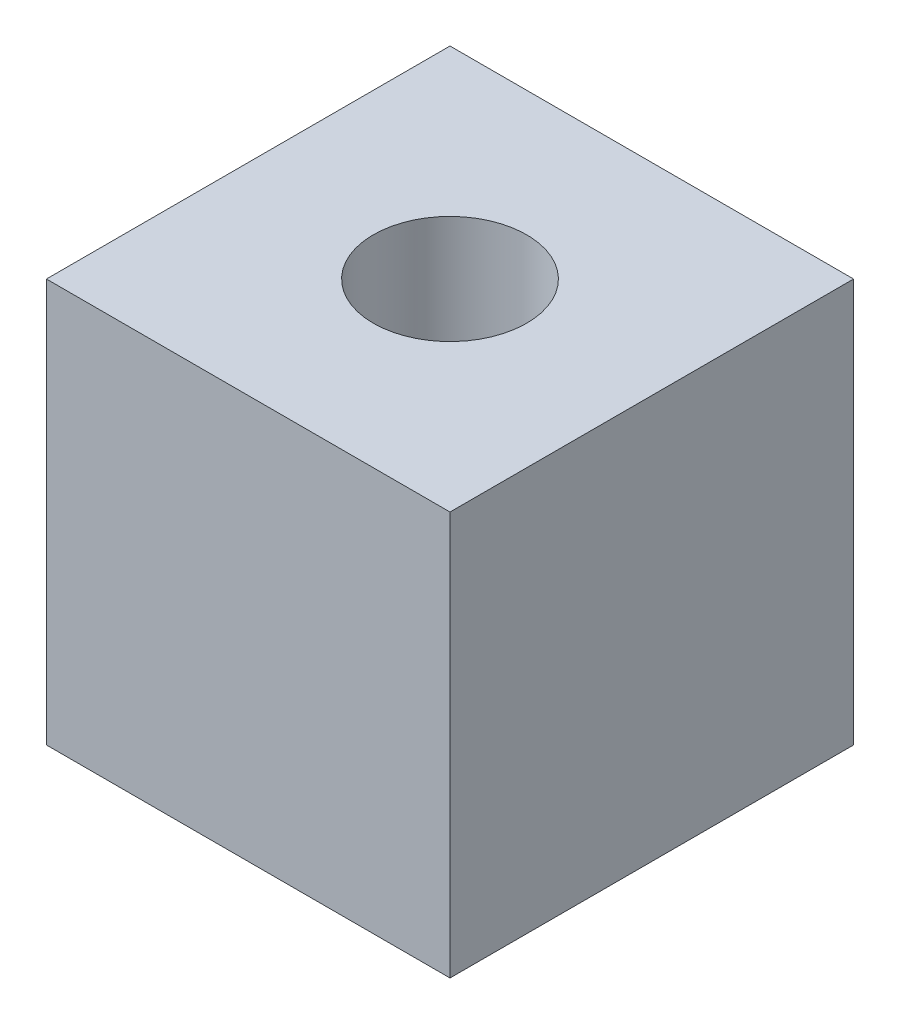
SolidWorks part; units mm, degrees
ref_plane "Front Plane" through (0, 0, 0) normal (0, 0, 1) x (1, 0, 0)
ref_plane "Top Plane" through (0, 0, 0) normal (0, 1, 0) x (1, 0, 0)
ref_plane "Right Plane" through (0, 0, 0) normal (1, 0, 0) x (0, 0, -1)
sketch "Sketch1" plane through (0, 0, 0) normal (0, 1, 0) x (1, 0, 0)
  line L1 (0, 0) -> (10, 0)
  line L2 (0, 0) -> (0, 10)
  line L3 (0, 10) -> (10, 10)
  line L4 (10, 0) -> (10, 10)
  dimension "D1" = 10
  dimension "D2" = 10
extrude "Boss-Extrude1" add sketch "Sketch1" along normal blind 10
sketch "Sketch2" plane through (0, 10, 0) normal (0, 1, 0) x (1, 0, 0)
  line L0 (5, 10) -> (5, 0) construction
  line L2 (10, 10) -> (0, 10) construction
  line L4 (0, 0) -> (10, 0) construction
  line L5 (0, 5) -> (10, 5) construction
  line L6 (0, 10) -> (0, 0) construction
  line L7 (10, 0) -> (10, 10) construction
  circle A0 centre (5, 5) radius 1.9
  point P14 (5, 5)
  dimension "D1" = 3.8
extrude "Cut-Extrude1" cut sketch "Sketch2" against normal blind 8.5
